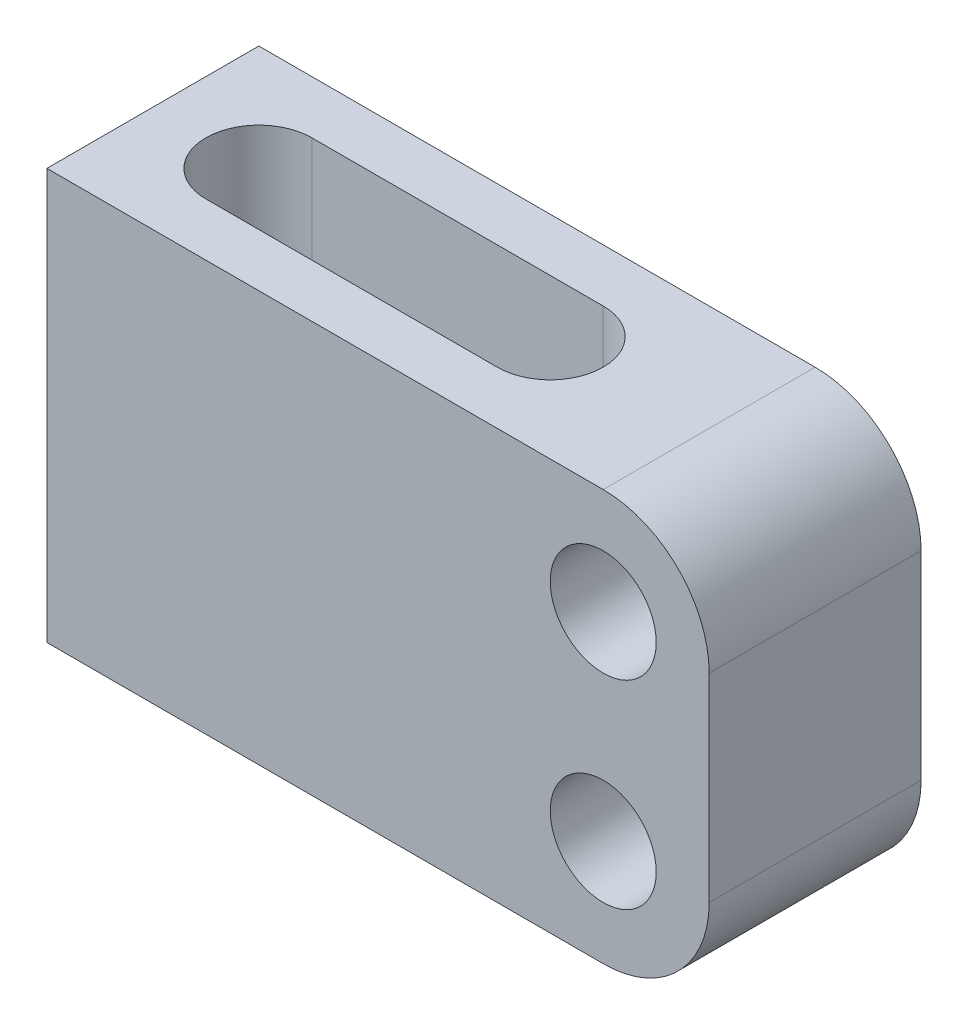
SolidWorks part; units mm, degrees
material "ABS"
ref_plane "Front Plane" through (0, 0, 0) normal (0, 0, 1) x (1, 0, 0)
ref_plane "Top Plane" through (0, 0, 0) normal (0, 1, 0) x (1, 0, 0)
ref_plane "Right Plane" through (0, 0, 0) normal (1, 0, 0) x (0, 0, -1)
sketch "Sketch1" plane through (0, 0, 0) normal (0, 0, 1) x (1, 0, 0)
  line L0 (0, 24.6616) -> (0, -42.6931) construction
  line L1 (8, 0) -> (8, -15)
  line L2 (0, 8) -> (-42, 8)
  line L3 (-42, 8) -> (-42, -23)
  line L4 (-42, -23) -> (0, -23)
  circle A0 centre (0, 0) radius 4
  circle A1 centre (0, -15) radius 4
  arc A2 (8, -15) -> (0, -23) centre (0, -15) cw
  arc A3 (8, 0) -> (0, 8) centre (0, 0) ccw
  dimension "D1" = 8
  dimension "D2" = 8
  dimension "D4" = 8
  dimension "D3" = 15
  dimension "D5" = 50
extrude "Boss-Extrude1" add sketch "Sketch1" against normal blind 16
sketch "Sketch2" plane through (0, 8, 0) normal (0, 1, 0) x (1, 0, 0)
  line L0 (-42, 8) -> (8, 8) construction
  line L1 (-42, 16) -> (-42, 0) construction
  line L2 (8, 16) -> (8, 0) construction
  line L3 (-34, 12) -> (-12, 12)
  line L4 (-34, 4) -> (-12, 4)
  arc A0 (-34, 12) -> (-34, 4) centre (-34, 8) ccw
  arc A1 (-12, 4) -> (-12, 12) centre (-12, 8) ccw
  dimension "D1" = 8
  dimension "D3" = 8
  dimension "D2" = 8
  dimension "D4" = 20
extrude "Cut-Extrude1" cut sketch "Sketch2" against normal through all
equation "\"rod_diameter\"= 8"
equation "\"rod_hole_thickness\"= 4"
equation "\"rod_radius\"= \"rod_diameter\" / 2"
equation "\"platter_diameter\"= 320"
equation "\"platter_radius\"= \"platter_diameter\" / 2"
equation "\"extruder_mount_hole_spacing\"= 75"
equation "\"arm_rod_spacing\"= 40"
equation "\"top_frame_rod_spacing\"= \"arm_rod_spacing\" + 40"
equation "\"motor_level_rod_spacing\"= 15"
equation "\"linear_bearing_diameter\"= 15"
equation "\"z_rod_spacing\"= 75"
equation "\"platter_rod_spacing\"= 50"
equation "\"rod_nut_thickness\"= 6.5"
equation "\"rod_nut_inscribed_diameter\"= 13"
equation "\"z_height\"= 350"
equation "\"D1@Sketch1\"=\"rod_diameter\""
equation "\"D2@Sketch1\"=\"rod_diameter\""
equation "\"D3@Sketch1\"=\"motor_level_rod_spacing\""
equation "\"D4@Sketch1\"=\"rod_radius\"+\"rod_hole_thickness\""
equation "\"D1@Boss-Extrude1\"= \"rod_diameter\" + \"rod_hole_thickness\" * 2"
equation "\"D1@Sketch2\"=\"rod_diameter\""
equation "\"D2@Sketch2\"=\"rod_radius\"+\"rod_hole_thickness\""
equation "\"D3@Sketch2\"=\"rod_diameter\""
equation "\"D4@Sketch2\"=\"rod_diameter\"+\"rod_hole_thickness\"*2 +\"rod_radius\""
